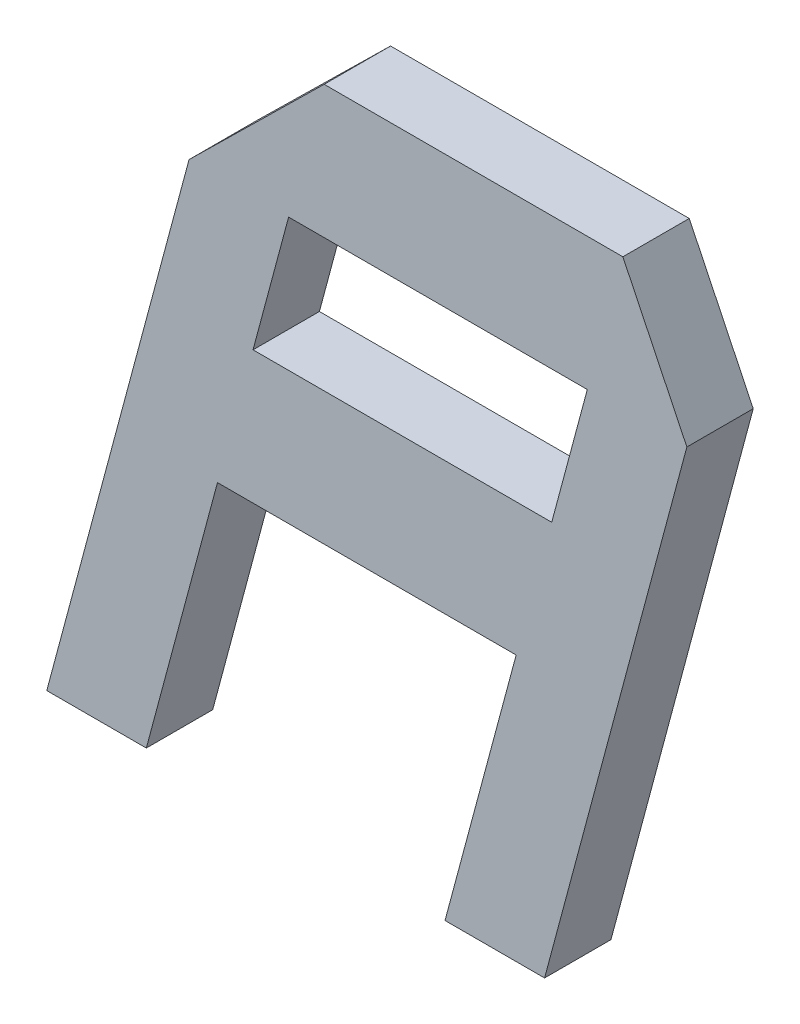
SolidWorks part; units mm, degrees
ref_plane "Přední rovina" through (0, 0, 0) normal (0, 0, 1) x (1, 0, 0)
ref_plane "Horní rovina" through (0, 0, 0) normal (0, 1, 0) x (1, 0, 0)
ref_plane "Pravá rovina" through (0, 0, 0) normal (1, 0, 0) x (0, 0, -1)
sketch "Skica1" plane through (0, 0, 0) normal (0, 0, 1) x (1, 0, 0)
  line L0 (0, 0) -> (26.7949, 100) construction
  line L1 (26.7949, 100) -> (41.7949, 100) construction
  line L3 (41.7949, 100) -> (86.7949, 100) construction
  line L4 (41.7949, 100) -> (15, 0) construction
  line L5 (86.7949, 100) -> (60, 0) construction
  line L6 (21.4359, 80) -> (96.4359, 80) construction
  line L7 (16.077, 60) -> (91.077, 60) construction
  line L8 (10.718, 40) -> (85.718, 40) construction
  line L9 (5.359, 20) -> (80.359, 20) construction
  line L10 (86.7949, 100) -> (101.7949, 100) construction
  line L11 (101.7949, 100) -> (96.4359, 80) construction
  line L12 (96.4359, 80) -> (91.077, 60) construction
  line L13 (91.077, 60) -> (85.718, 40) construction
  line L14 (85.718, 40) -> (80.359, 20) construction
  line L15 (80.359, 20) -> (75, 0) construction
  line L16 (75, 0) -> (0, 0) construction
  point P3 (36.4359, 80)
  point P5 (81.4359, 80)
  point P19 (31.077, 60)
  point P20 (76.077, 60)
  point P21 (70.718, 40)
  point P22 (25.718, 40)
  point P23 (20.359, 20)
  point P24 (65.359, 20)
  dimension "D1" = 75
  dimension "D2" = 100
  dimension "D3" = 75
  dimension "D4" = 20
  dimension "D5" = 15
sketch "Skica5" plane through (0, 0, 0) normal (0, 0, 1) x (1, 0, 0)
  line L0 (0, 0) -> (21.4359, 80)
  line L1 (21.4359, 80) -> (41.7949, 100)
  line L2 (41.7949, 100) -> (86.7949, 100)
  line L3 (15, 0) -> (0, 0)
  line L4 (75, 0) -> (60, 0)
  line L5 (36.4359, 80) -> (81.4359, 80)
  line L6 (60, 0) -> (70.718, 40)
  line L7 (70.718, 40) -> (25.718, 40)
  line L8 (25.718, 40) -> (15, 0)
  line L9 (86.7949, 100) -> (96.4359, 80)
  line L10 (36.4359, 80) -> (31.077, 60)
  line L11 (96.4359, 80) -> (75, 0)
  line L12 (31.077, 60) -> (76.077, 60)
  line L16 (76.077, 60) -> (81.4359, 80)
extrude "A_" add sketch "Skica5" along normal blind 10
sketch "Skica6" [suppressed] plane through (0, 0, 0) normal (0, 0, 1) x (1, 0, 0)
  line L0 (19.0555, 23) -> (15, 0)
  line L1 (15, 0) -> (75, 0)
  line L2 (75, 0) -> (79.0555, 23)
  line L3 (79.0555, 23) -> (19.0555, 23)
  line L4 (21.7886, 38.5) -> (25.8441, 61.5)
  line L5 (25.8441, 61.5) -> (70.8441, 61.5)
  line L6 (70.8441, 61.5) -> (66.7886, 38.5)
  line L7 (66.7886, 38.5) -> (21.7886, 38.5)
  line L8 (17.6327, 100) -> (13.5772, 77)
  line L9 (13.5772, 77) -> (73.5772, 77)
  line L10 (73.5772, 77) -> (77.6327, 100)
  line L11 (77.6327, 100) -> (17.6327, 100)
extrude "E" [suppressed] add sketch "Skica6" along normal blind 10
sketch "Skica7" [suppressed] plane through (0, 0, 0) normal (0, 0, 1) x (1, 0, 0)
  line L0 (0, 0) -> (21.4359, 80)
  line L1 (21.4359, 80) -> (41.7949, 100)
  line L2 (41.7949, 100) -> (86.7949, 100)
  line L3 (86.7949, 100) -> (96.4359, 80)
  line L4 (25.718, 40) -> (15, 0)
  line L5 (15, 0) -> (0, 0)
  line L6 (36.4359, 80) -> (31.077, 60)
  line L7 (31.077, 60) -> (76.077, 60)
  line L8 (76.077, 60) -> (81.4359, 80)
  line L9 (81.4359, 80) -> (36.4359, 80)
  line L10 (25.718, 40) -> (60, 0)
  line L11 (60, 0) -> (75, 0)
  line L12 (75, 0) -> (80.359, 20)
  line L13 (80.359, 20) -> (65.359, 20)
  line L14 (65.359, 20) -> (48.218, 40)
  line L15 (96.4359, 80) -> (91.077, 60)
  line L16 (91.077, 60) -> (70.718, 40)
  line L17 (70.718, 40) -> (48.218, 40)
  line L20 (91.077, 60) -> (85.718, 40) construction
extrude "R" [suppressed] add sketch "Skica7" along normal blind 10
sketch "Skica8" [suppressed] plane through (0, 0, 0) normal (0, 0, 1) x (1, 0, 0)
  line L0 (32.6327, 100) -> (17.6327, 100)
  line L1 (17.6327, 100) -> (0, 0)
  line L2 (0, 0) -> (75, 0)
  line L3 (75, 0) -> (92.6327, 100)
  line L4 (92.6327, 100) -> (77.6327, 100)
  line L5 (77.6327, 100) -> (64.0555, 23)
  line L6 (64.0555, 23) -> (19.0555, 23)
  line L7 (19.0555, 23) -> (32.6327, 100)
extrude "U" [suppressed] add sketch "Skica8" along normal blind 10
